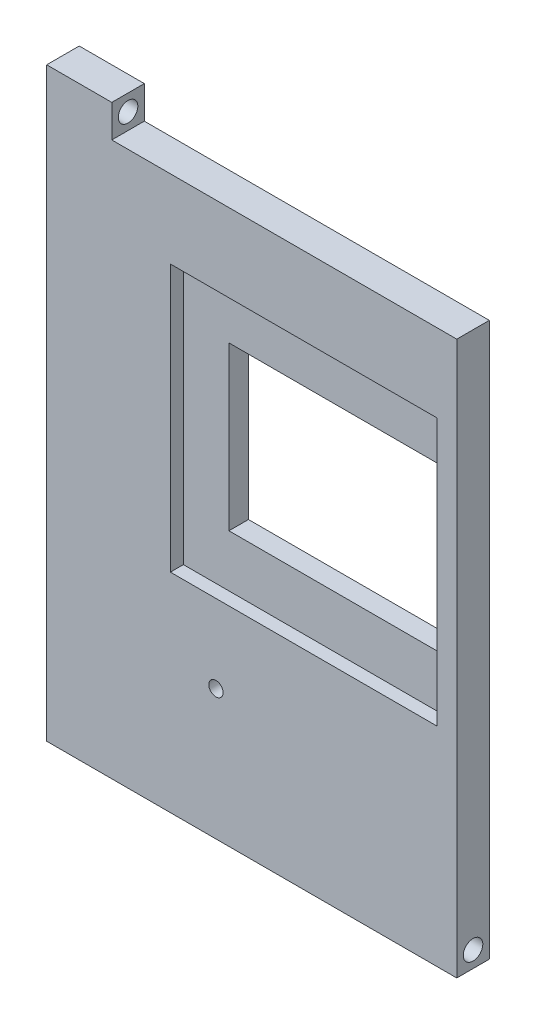
SolidWorks part; units mm, degrees
material "Alliage 1060"
ref_plane "Plan de dessus" through (0, 0, 0) normal (0, 0, 1) x (1, 0, 0)
ref_plane "Plan de droite" through (0, 0, 0) normal (0, 1, 0) x (1, 0, 0)
ref_plane "Plan de face" through (0, 0, 0) normal (1, 0, 0) x (0, 0, -1)
sketch "Esquisse1" plane through (0, 0, 0) normal (0, 0, 1) x (1, 0, 0)
  line L44 (0, 0) -> (0, 85)
  line L49 (63, 0) -> (0, 0)
  line L68 (63, 0) -> (63, 85)
  line L70 (63, 85) -> (10, 85)
  line L71 (10, 85) -> (10, 90)
  line L72 (10, 90) -> (0, 90)
  line L73 (0, 90) -> (0, 85)
  dimension "D1" = 85
  dimension "D2" = 53
  dimension "D3" = 5
  dimension "D4" = 10
extrude "Boss.-Extru.1" add sketch "Esquisse1" along normal blind 5
sketch "Esquisse6" plane through (0, 0, 0) normal (0, 0, -1) x (-1, 0, 0)
  line L1 (0, 90) -> (0, 0) construction
  line L2 (0, 0) -> (-63, 0) construction
  circle A0 centre (-26, 20) radius 1.1
  dimension "D1" = 26
  dimension "D3" = 2.2
  dimension "D2" = 20
sketch "Esquisse8" plane through (0, 0, 0) normal (0, 0, -1) x (-1, 0, 0)
  line L0 (0, 0) -> (-63, 0) construction
  line L5 (-63, 0) -> (-63, 85) construction
  line L6 (-60, 65) -> (-26, 65)
  line L7 (-26, 65) -> (-26, 40)
  line L8 (-60, 40) -> (-26, 40)
  line L9 (-60, 65) -> (-60, 40)
  dimension "D1" = 40
  dimension "D2" = 25
  dimension "D3" = 34
  dimension "D4" = 3
extrude "Enlèv. mat.-Extru.6" cut sketch "Esquisse8" against normal up to surface (5 mm away) contours L6 L7 L8 L9 up to face at (24.3333, 58.3333, 5)
sketch "Esquisse9" plane through (0, 0, 0) normal (0, 0, -1) x (-1, 0, 0)
  line L1 (-60, 73) -> (-19, 73)
  line L2 (-60, 73) -> (-60, 32)
  line L3 (-60, 32) -> (-19, 32)
  line L4 (-19, 73) -> (-19, 32)
  line L6 (-60, 65) -> (-60, 40) construction
  line L7 (-63.3417, 65) -> (-63.3417, 73) construction
  line L8 (-60, 65) -> (-26, 65) construction
  line L9 (-63.3417, 40) -> (-63.3417, 32) construction
  line L10 (-60, 40) -> (-26, 40) construction
  dimension "D1" = 41
  dimension "D2" = 41
extrude "Enlèv. mat.-Extru.7" cut sketch "Esquisse9" along normal blind 2 from surface at -5 starting at face at (43, 52.5, 5)
sketch "Esquisse10" plane through (0, 0, 0) normal (-1, 0, 0) x (0, 0, 1)
  line L0 (5, 90) -> (0, 90) construction
  line L1 (5, 90) -> (5, 0) construction
  circle A0 centre (2.5, 87.5) radius 1.5
  dimension "D1" = 3
  dimension "D2" = 2.5
  dimension "D3" = 2.5
extrude "Enlèv. mat.-Extru.8" cut sketch "Esquisse10" against normal up to next
sketch "Esquisse12" plane through (63, 0, 0) normal (1, 0, 0) x (0, 0, -1)
  line L0 (0, 0) -> (0, 85) construction
  line L1 (-5, 0) -> (0, 0) construction
  circle A0 centre (-2.5, 2.5) radius 1.5
  dimension "D1" = 3
  dimension "D2" = 2.5
  dimension "D3" = 2.5
extrude "Enlèv. mat.-Extru.10" cut sketch "Esquisse12" against normal blind 15
extrude "Enlèv. mat.-Extru.11" cut sketch "Esquisse6" against normal up to next
